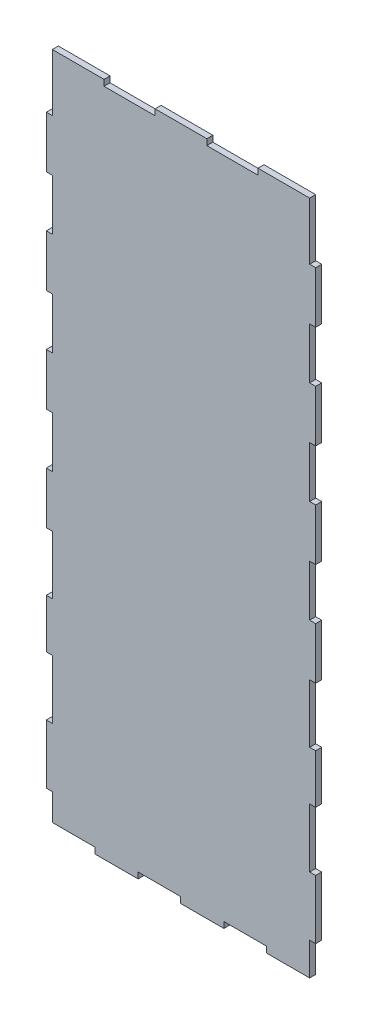
SolidWorks part; units mm, degrees
ref_plane "Front Plane" through (0, 0, 0) normal (0, 0, 1) x (1, 0, 0)
ref_plane "Top Plane" through (0, 0, 0) normal (0, 1, 0) x (1, 0, 0)
ref_plane "Right Plane" through (0, 0, 0) normal (1, 0, 0) x (0, 0, -1)
sketch "Sketch1" plane through (0, 0, 0) normal (0, 0, 1) x (1, 0, 0)
  line L0 (64.15, 153.0192) -> (64.15, 178.4819)
  line L1 (64.15, 204.2445) -> (64.15, 229.7071)
  line L2 (64.15, 255.4698) -> (64.15, 280.9324)
  line L3 (64.15, 306.6951) -> (64.15, 281.2324) construction
  line L4 (64.15, 281.2324) -> (64.15, 280.9324) construction
  line L5 (-64.15, 280.9324) -> (-64.15, 255.4698)
  line L6 (-64.15, 229.7071) -> (-64.15, 204.2445)
  line L7 (-64.15, 178.4819) -> (-64.15, 153.0192)
  line L8 (64.15, 98.1217) -> (67.15, 98.1217)
  line L9 (67.15, 98.1217) -> (67.15, 73.6732)
  line L10 (67.15, 73.6732) -> (64.15, 73.6732)
  line L11 (64.15, 73.6732) -> (64.15, 44.2746)
  line L12 (64.15, 44.2746) -> (67.15, 44.2746)
  line L13 (67.15, 44.2746) -> (67.15, 14.826)
  line L14 (67.15, 14.826) -> (64.15, 14.826)
  line L15 (64.15, 14.826) -> (64.15, -1.5)
  line L23 (64.15, 98.1217) -> (64.15, 73.9732) construction
  line L24 (64.15, 73.9732) -> (64.15, 73.6732) construction
  line L25 (0, 265.3273) -> (0, -93.4505) construction
  line L26 (-259.4583, 0) -> (-323.6083, 0) construction
  line L34 (-64.15, 14.826) -> (-64.15, 1.5)
  line L35 (-67.15, 14.826) -> (-64.15, 14.826)
  line L36 (-67.15, 44.2746) -> (-67.15, 14.826)
  line L37 (-64.15, 44.2746) -> (-67.15, 44.2746)
  line L38 (-67.15, 73.6732) -> (-64.15, 73.6732)
  line L39 (-64.15, 73.6732) -> (-64.15, 44.2746)
  line L40 (-67.15, 98.1217) -> (-67.15, 73.6732)
  line L42 (12.89, 335.2619) -> (12.89, 332.2619)
  line L43 (12.89, 332.2619) -> (38.37, 332.2619)
  line L44 (38.37, 332.2619) -> (38.37, 335.2619)
  line L46 (-38.37, 335.2619) -> (-38.37, 332.2619)
  line L47 (-38.37, 332.2619) -> (-12.89, 332.2619)
  line L48 (-12.89, 332.2619) -> (-12.89, 335.2619)
  line L49 (-67.15, 280.9324) -> (-64.15, 280.9324)
  line L51 (-64.15, 306.6951) -> (-67.15, 306.6951)
  line L52 (-67.15, 306.6951) -> (-67.15, 280.9324)
  line L53 (-67.15, 229.7071) -> (-64.15, 229.7071)
  line L55 (-64.15, 255.4698) -> (-67.15, 255.4698)
  line L56 (-67.15, 255.4698) -> (-67.15, 229.7071)
  line L57 (-67.15, 178.4819) -> (-64.15, 178.4819)
  line L59 (-64.15, 204.2445) -> (-67.15, 204.2445)
  line L60 (-67.15, 204.2445) -> (-67.15, 178.4819)
  line L62 (-64.15, 153.0192) -> (-67.15, 153.0192)
  line L63 (-67.15, 153.0192) -> (-67.15, 127.2566)
  line L64 (-67.15, 127.2566) -> (-64.15, 127.2566)
  line L65 (67.15, 127.2566) -> (67.15, 153.0192)
  line L66 (67.15, 153.0192) -> (64.15, 153.0192)
  line L68 (64.15, 127.2566) -> (67.15, 127.2566)
  line L69 (64.15, 229.7071) -> (67.15, 229.7071)
  line L70 (67.15, 229.7071) -> (67.15, 255.4698)
  line L71 (67.15, 255.4698) -> (64.15, 255.4698)
  line L73 (64.15, 280.9324) -> (67.15, 280.9324)
  line L74 (67.15, 280.9324) -> (67.15, 306.6951)
  line L75 (67.15, 306.6951) -> (64.15, 306.6951)
  line L77 (64.15, 98.1217) -> (64.15, 127.2566)
  line L78 (-64.15, 98.1217) -> (-64.15, 127.2566)
  line L79 (64.15, 335.2619) -> (38.37, 335.2619)
  line L80 (12.89, 335.2619) -> (-12.89, 335.2619)
  line L81 (-38.37, 335.2619) -> (-64.15, 335.2619)
  line L82 (64.15, 335.2619) -> (64.15, 306.6951)
  line L83 (-64.15, 335.2619) -> (-64.15, 306.6951)
  line L84 (-38.37, 332.2619) -> (-38.67, 332.2619) construction
  line L85 (-38.67, 332.2619) -> (-64.15, 332.2619) construction
  line L86 (-64.15, 98.1217) -> (-67.15, 98.1217)
  line L90 (64.15, 178.4819) -> (67.15, 178.4819)
  line L91 (67.15, 178.4819) -> (67.15, 204.2445)
  line L92 (67.15, 204.2445) -> (64.15, 204.2445)
  line L137 (64.15, -1.5) -> (42.6167, -1.5)
  line L138 (42.6167, -1.5) -> (42.6167, 1.5)
  line L139 (42.6167, 1.5) -> (21.3833, 1.5)
  line L140 (21.3833, 1.5) -> (21.3833, -1.5)
  line L141 (-0.15, -1.5) -> (-0.15, 1.5)
  line L142 (-0.15, 1.5) -> (-21.3833, 1.5)
  line L143 (-21.3833, 1.5) -> (-21.3833, -1.5)
  line L144 (-21.3833, -1.5) -> (-42.9167, -1.5)
  line L145 (-42.9167, -1.5) -> (-42.9167, 1.5)
  line L146 (-42.9167, 1.5) -> (-64.15, 1.5)
  line L147 (-0.15, -1.5) -> (21.3833, -1.5)
  line L148 (42.6167, 1.5) -> (63.85, 1.5) construction
  line L149 (63.85, 1.5) -> (64.15, 1.5) construction
  point P39 (0, 335.2619)
  point P47 (64.15, 0)
  point P143 (42.6167, 0)
  dimension "D1" = 0.3
  dimension "D2" = 128.3
  dimension "D3" = 3
  dimension "D4" = 28.5669
  dimension "D5" = 29.1349
  dimension "D6" = 179.4385
  dimension "D7" = 24.4486
  dimension "D8" = 0.3
  dimension "D9" = 29.3986
  dimension "D10" = 29.4486
  dimension "D11" = 13.326
  dimension "D12" = 336.7619
extrude "Boss-Extrude1" add sketch "Sketch1" along normal blind 3
